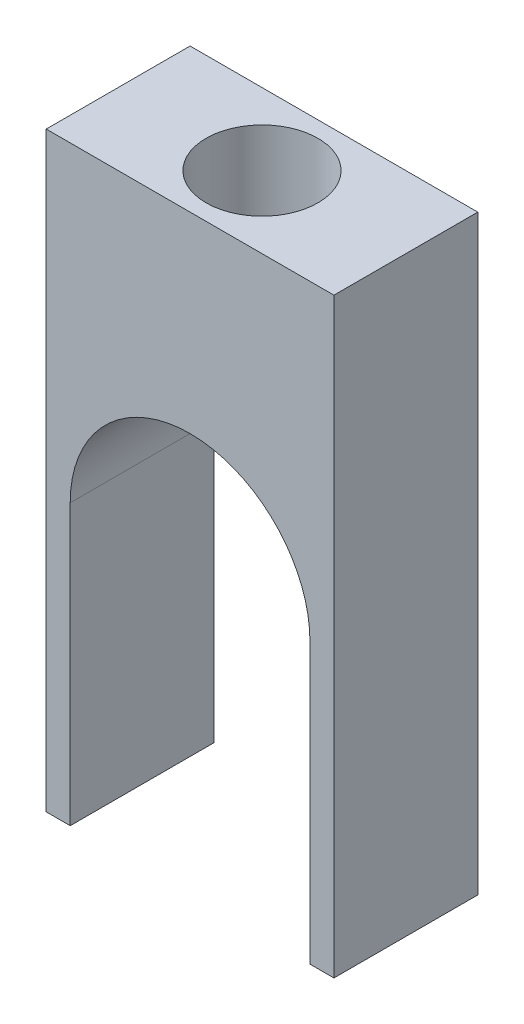
SolidWorks part; units mm, degrees
ref_plane "Front Plane" through (0, 0, 0) normal (0, 0, 1) x (1, 0, 0)
ref_plane "Top Plane" through (0, 0, 0) normal (0, 1, 0) x (1, 0, 0)
ref_plane "Right Plane" through (0, 0, 0) normal (1, 0, 0) x (0, 0, -1)
sketch "Sketch2" plane through (0, 0, 0) normal (0, 0, 1) x (1, 0, 0)
  line L0 (-21, 22) -> (-50021, 22) construction
  line L1 (-36, 74) -> (0, 74)
  line L2 (-36, 74) -> (-36, 0)
  line L3 (-36, 0) -> (0, 0)
  line L4 (0, 74) -> (0, 0)
  line L5 (-33.3871, 74) -> (-12.6168, 74)
  line L6 (-33, 35) -> (-33, 0)
  line L7 (-33, 0) -> (-3, 0)
  line L8 (-3, 35) -> (-3, 0)
  line L9 (-21, 28) -> (-50021, 28) construction
  arc A0 (-3, 35) -> (-33, 35) centre (-18, 35) ccw
  circle A1 centre (-18, 25) radius 3 construction
  circle A2 centre (-18, 35) radius 15 construction
  circle A3 centre (-18, 15) radius 15 construction
  point P11 (-18, 74)
  point P12 (-35, 35)
  point P23 (0, 0)
  point P24 (-18, 26.6773)
  dimension "D2" = 30
  dimension "D5" = 6
  dimension "D8" = 30
  dimension "D1" = 3
  dimension "D3" = 74
  dimension "D4" = 7
  dimension "D6" = 7
extrude "Boss-Extrude1" add sketch "Sketch2" along normal blind 18 contours L6 L1 L2 L3 | A0 L8 L1 L6 | L1 L8 L3 L4
sketch "Sketch3" plane through (0, 74, 0) normal (0, 1, 0) x (1, 0, 0)
  line L0 (-36, -18) -> (-36, 0) construction
  line L1 (-36, 0) -> (0, 0) construction
  circle A0 centre (-18, -9) radius 7
  point P2 (-36, -9)
  point P3 (-18, 0)
  dimension "D1" = 14
  dimension "D2" = 18
extrude "Cut-Extrude1" cut sketch "Sketch3" against normal up to surface (24 mm away)
